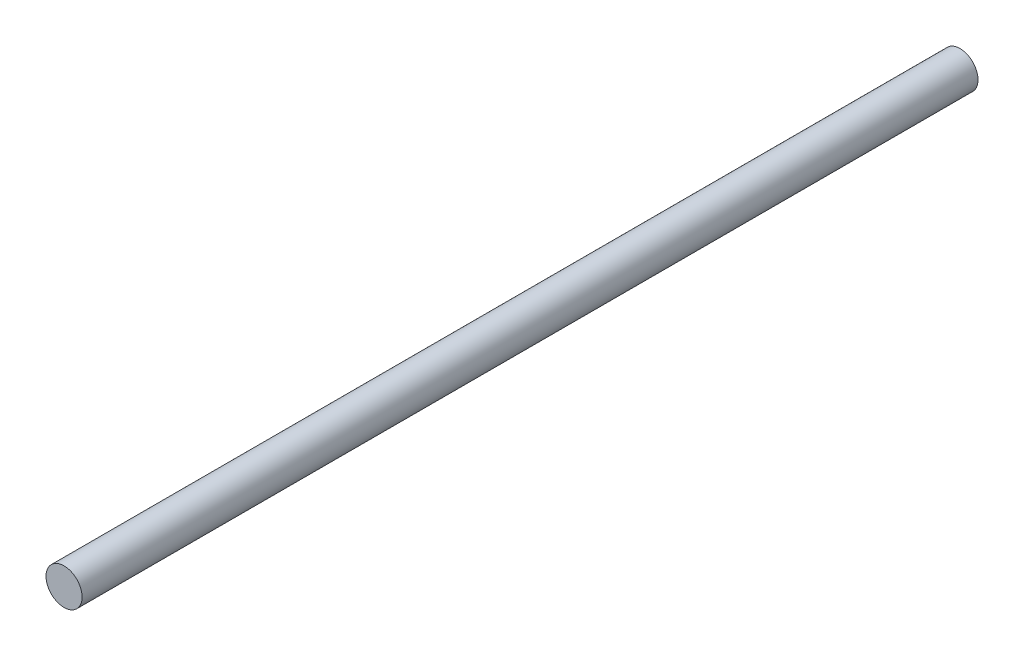
SolidWorks part; units mm, degrees
ref_plane "Front Plane" through (0, 0, 0) normal (0, 0, 1) x (1, 0, 0)
ref_plane "Top Plane" through (0, 0, 0) normal (0, 1, 0) x (1, 0, 0)
ref_plane "Right Plane" through (0, 0, 0) normal (1, 0, 0) x (0, 0, -1)
sketch "Sketch1" plane through (0, 0, 0) normal (0, 0, 1) x (1, 0, 0)
  circle A0 centre (0, 0) radius 4.7625
  dimension "D1" = 9.525
extrude "Boss-Extrude1" add sketch "Sketch1" along normal mid plane 236.5
